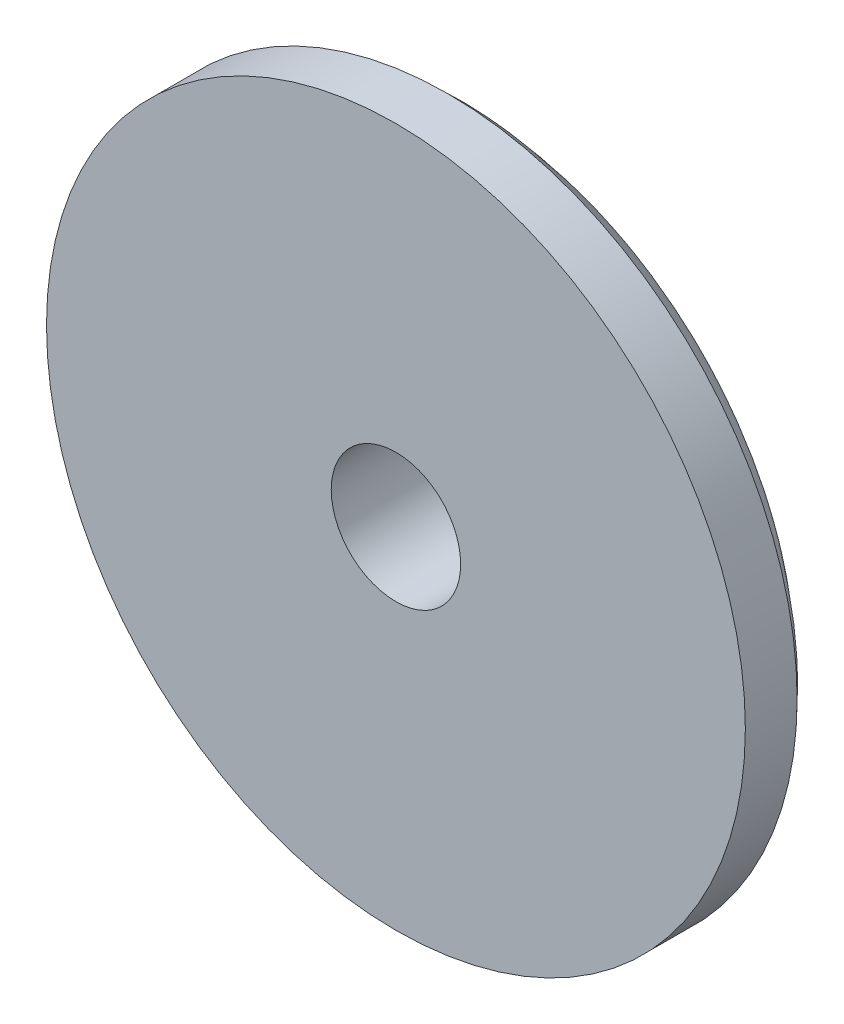
SolidWorks part; units mm, degrees
ref_plane "前视基准面" through (0, 0, 0) normal (0, 0, 1) x (1, 0, 0)
ref_plane "上视基准面" through (0, 0, 0) normal (0, 1, 0) x (1, 0, 0)
ref_plane "右视基准面" through (0, 0, 0) normal (1, 0, 0) x (0, 0, -1)
sketch "草图1" plane through (0, 0, 0) normal (0, 0, 1) x (1, 0, 0)
  circle A0 centre (0, 0) radius 13.5
  dimension "D1" = 27
extrude "凸台-拉伸1" add sketch "草图1" along normal blind 2
sketch "草图3" plane through (0, 0, 0) normal (0, 0, -1) x (-1, 0, 0)
  circle A2 centre (0, 0) radius 8.5
  circle A3 centre (0, 0) radius 8.5
  dimension "D1" = 5
extrude "凸台-拉伸2" add sketch "草图3" along normal blind 2.5
sketch "草图4" plane through (0, 0, 0) normal (0, 1, 0) x (1, 0, 0)
  line L0 (-13.5, 0) -> (-8.5, 2.5)
  arc A0 (-13.5, 0) -> (-8.5, 2.5) centre (-7.9079, -4.9341) cw
sweep "扫描1" add profiles "草图4" path edge at (-8.5, 0, -2.5)
sketch "草图7" plane through (0, 0, -2.5) normal (0, 0, -1) x (-1, 0, 0)
  circle A0 centre (0, 0) radius 2.5
  dimension "D1" = 5
extrude "切除-拉伸1" cut sketch "草图7" against normal up to next (4.5 mm away)
